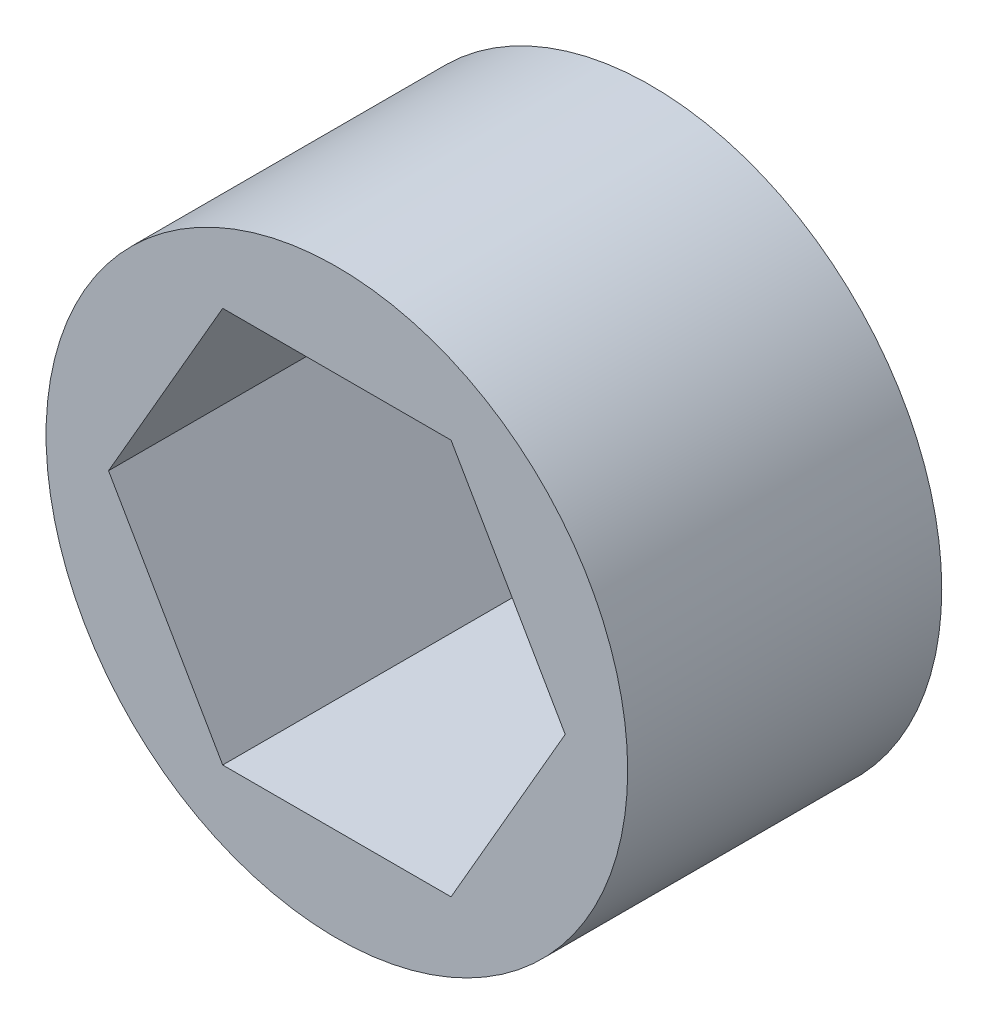
SolidWorks part; units mm, degrees
material "PET"
ref_plane "Front Plane" through (0, 0, 0) normal (0, 0, 1) x (1, 0, 0)
ref_plane "Top Plane" through (0, 0, 0) normal (0, 1, 0) x (1, 0, 0)
ref_plane "Right Plane" through (0, 0, 0) normal (1, 0, 0) x (0, 0, -1)
sketch "Sketch1" plane through (0, 0, 0) normal (0, 0, 1) x (1, 0, 0)
  line L7 (7.479, 0) -> (3.7395, 6.477)
  line L8 (3.7395, 6.477) -> (-3.7395, 6.477)
  line L9 (-3.7395, 6.477) -> (-7.479, 0)
  line L10 (-7.479, 0) -> (-3.7395, -6.477)
  line L11 (-3.7395, -6.477) -> (3.7395, -6.477)
  line L12 (3.7395, -6.477) -> (7.479, 0)
  circle A2 centre (0, 0) radius 6.477 construction
  circle A3 centre (0, 0) radius 9.525
  dimension "D1" = 19.05
  dimension "D2" = 12.954
extrude "Boss-Extrude1" add sketch "Sketch1" along normal mid plane 10.287
equation "\"D1@Boss-Extrude1\"=0.405"
